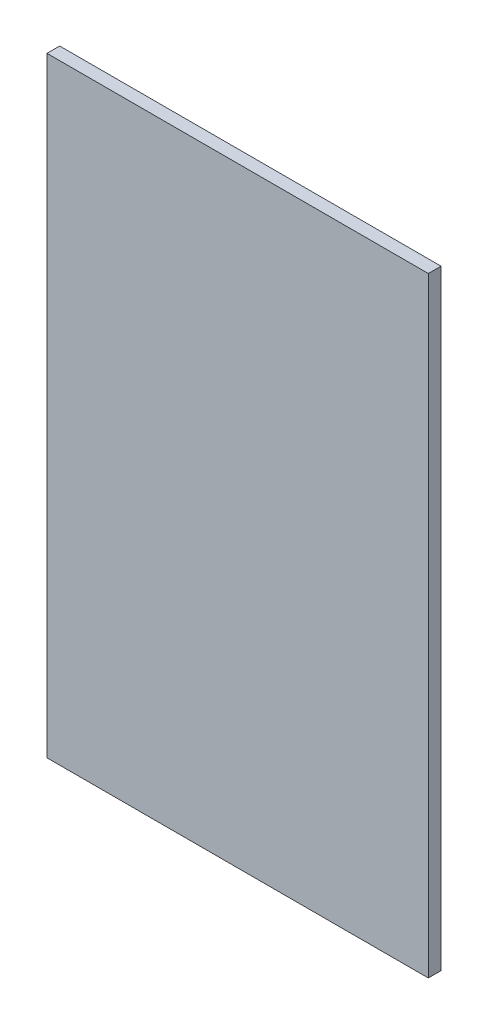
SolidWorks part; units mm, degrees
ref_plane "Plan de face" through (0, 0, 0) normal (0, 0, 1) x (1, 0, 0)
ref_plane "Plan de dessus" through (0, 0, 0) normal (0, 1, 0) x (1, 0, 0)
ref_plane "Plan de droite" through (0, 0, 0) normal (1, 0, 0) x (0, 0, -1)
sketch "Esquisse1" plane through (0, 0, 0) normal (0, 0, 1) x (1, 0, 0)
  line L1 (-105, -120) -> (105, -120)
  line L2 (-105, -120) -> (-105, 120)
  line L3 (-105, 120) -> (105, 120)
  line L4 (105, -120) -> (105, 120)
  line L5 (-105, -120) -> (105, 120) construction
  line L6 (-105, 120) -> (105, -120) construction
  point P0 (0, 0)
  dimension "D1" = 210
  dimension "D2" = 240
extrude "Boss.-Extru.1" add sketch "Esquisse1" along normal blind 5
sketch "Esquisse2" plane through (0, 0, 0) normal (0, 0, -1) x (-1, 0, 0)
  line L0 (0, 120) -> (0, -120) construction
  line L1 (-105, 120) -> (105, 120) construction
  line L2 (105, -120) -> (-105, -120) construction
  line L3 (0, 0) -> (-105, 0) construction
  line L4 (-40, 195) -> (40, 195)
  line L5 (-40, 195) -> (-40, 45)
  line L6 (-40, 45) -> (40, 45)
  line L7 (40, 195) -> (40, 45)
  line L8 (-40, 195) -> (40, 45) construction
  line L9 (-40, 45) -> (40, 195) construction
  line L10 (-105, -120) -> (-105, 120) construction
  line L11 (-40, -195) -> (40, -195)
  line L12 (-40, -195) -> (-40, -45)
  line L13 (40, -195) -> (40, -45)
  line L14 (-40, -45) -> (40, -45)
  dimension "D1" = 150
  dimension "D2" = 80
extrude "Enlèv. mat.-Extru.1" [suppressed] cut sketch "Esquisse2" against normal blind 5
sketch "Esquisse3" plane through (0, 0, 5) normal (0, 0, 1) x (1, 0, 0)
  line L0 (105, -120) -> (105, 120) construction
  line L1 (165, -120) -> (45, -120)
  line L2 (165, -120) -> (165, 120)
  line L3 (165, 120) -> (45, 120)
  line L4 (45, -120) -> (45, 120)
  line L5 (165, -120) -> (45, 120) construction
  line L6 (165, 120) -> (45, -120) construction
  line L7 (-105, -120) -> (105, -120) construction
  point P0 (105, 0)
  dimension "D1" = 120
extrude "Enlèv. mat.-Extru.2" cut sketch "Esquisse3" against normal through all
equation "\"X\"= 300mm"
equation "\"Y\"= 250mm"
